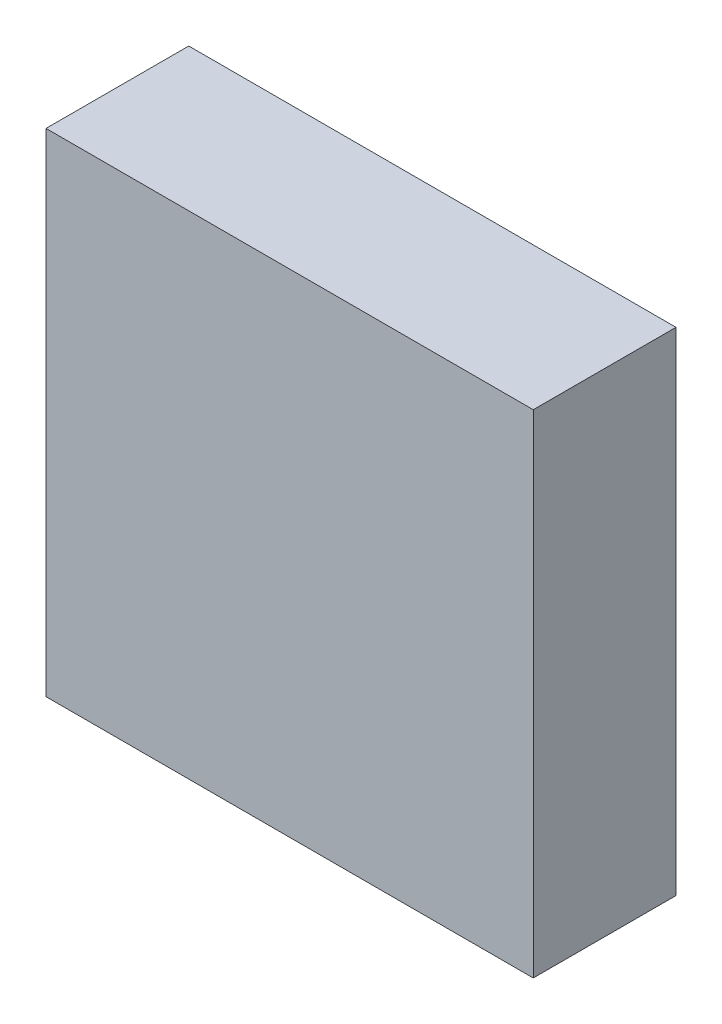
SolidWorks part; units mm, degrees
material "Cast Alloy Steel"
ref_plane "Front Plane" through (0, 0, 0) normal (0, 0, 1) x (1, 0, 0)
ref_plane "Top Plane" through (0, 0, 0) normal (0, 1, 0) x (1, 0, 0)
ref_plane "Right Plane" through (0, 0, 0) normal (1, 0, 0) x (0, 0, -1)
sketch "Sketch1" plane through (0, 0, 0) normal (0, 1, 0) x (1, 0, 0)
  line L1 (0, 0) -> (1257.3, 0)
  line L2 (0, 0) -> (0, 368.3)
  line L3 (0, 368.3) -> (1257.3, 368.3)
  line L4 (1257.3, 0) -> (1257.3, 368.3)
  dimension "D1" = 1257.3
  dimension "D2" = 368.3
extrude "Extrude1" add sketch "Sketch1" along normal blind 1270
